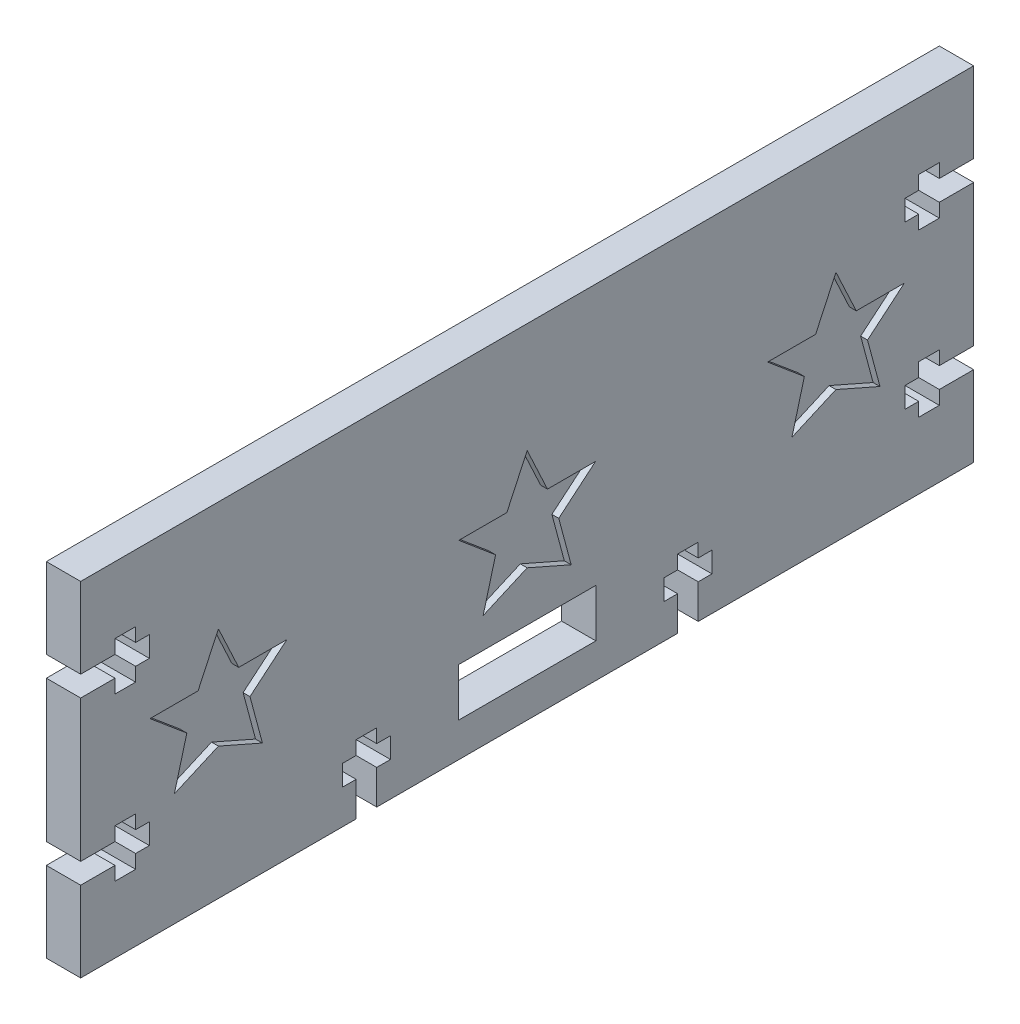
SolidWorks part; units mm, degrees
ref_plane "Front Plane" through (0, 0, 0) normal (0, 0, 1) x (1, 0, 0)
ref_plane "Top Plane" through (0, 0, 0) normal (0, 1, 0) x (1, 0, 0)
ref_plane "Right Plane" through (0, 0, 0) normal (1, 0, 0) x (0, 0, -1)
sketch "Sketch1" plane through (0, 0, 0) normal (1, 0, 0) x (0, 0, -1)
  line L0 (0, -14.859) -> (0, -18.669) construction
  line L1 (0, 0) -> (165.1, 0)
  line L2 (0, 0) -> (0, -14.859)
  line L3 (0, -63.5) -> (165.1, -63.5)
  line L4 (165.1, 0) -> (165.1, -14.859)
  line L5 (0, -18.669) -> (6.35, -18.669)
  line L6 (0, -18.669) -> (0, -14.859) construction
  line L7 (0, -14.859) -> (6.35, -14.859)
  line L8 (12.7, -18.669) -> (12.7, -14.859)
  line L9 (0, -48.641) -> (6.35, -48.641)
  line L10 (0, -48.641) -> (0, -44.831) construction
  line L11 (0, -44.831) -> (6.35, -44.831)
  line L12 (12.7, -48.641) -> (12.7, -44.831)
  line L13 (6.35, -12.319) -> (10.16, -12.319)
  line L14 (6.35, -12.319) -> (6.35, -14.859)
  line L15 (6.35, -21.209) -> (10.16, -21.209)
  line L16 (10.16, -12.319) -> (10.16, -14.859)
  line L17 (6.35, -42.291) -> (10.16, -42.291)
  line L18 (6.35, -42.291) -> (6.35, -44.831)
  line L19 (6.35, -51.181) -> (10.16, -51.181)
  line L20 (10.16, -42.291) -> (10.16, -44.831)
  line L21 (165.1, -14.859) -> (158.75, -14.859)
  line L22 (165.1, -14.859) -> (165.1, -18.669) construction
  line L23 (165.1, -18.669) -> (158.75, -18.669)
  line L24 (152.4, -14.859) -> (152.4, -18.669)
  line L25 (154.94, -12.319) -> (158.75, -12.319)
  line L26 (154.94, -12.319) -> (154.94, -14.859)
  line L27 (154.94, -21.209) -> (158.75, -21.209)
  line L28 (158.75, -12.319) -> (158.75, -14.859)
  line L29 (165.1, -44.831) -> (158.75, -44.831)
  line L30 (165.1, -44.831) -> (165.1, -48.641) construction
  line L31 (165.1, -48.641) -> (158.75, -48.641)
  line L32 (152.4, -44.831) -> (152.4, -48.641)
  line L33 (154.94, -42.291) -> (158.75, -42.291)
  line L34 (154.94, -42.291) -> (154.94, -44.831)
  line L35 (154.94, -51.181) -> (158.75, -51.181)
  line L36 (158.75, -42.291) -> (158.75, -44.831)
  line L37 (0, -18.669) -> (0, -44.831)
  line L38 (6.35, -14.859) -> (6.35, -18.669) construction
  line L39 (6.35, -18.669) -> (6.35, -21.209)
  line L40 (10.16, -14.859) -> (10.16, -18.669) construction
  line L41 (10.16, -18.669) -> (10.16, -21.209)
  line L42 (6.35, -14.859) -> (10.16, -14.859) construction
  line L43 (10.16, -14.859) -> (12.7, -14.859)
  line L44 (6.35, -18.669) -> (10.16, -18.669) construction
  line L45 (10.16, -18.669) -> (12.7, -18.669)
  line L46 (0, -44.831) -> (0, -48.641) construction
  line L47 (0, -48.641) -> (0, -63.5)
  line L48 (6.35, -44.831) -> (6.35, -48.641) construction
  line L49 (6.35, -48.641) -> (6.35, -51.181)
  line L50 (10.16, -44.831) -> (10.16, -48.641) construction
  line L51 (10.16, -48.641) -> (10.16, -51.181)
  line L52 (6.35, -44.831) -> (10.16, -44.831) construction
  line L53 (10.16, -44.831) -> (12.7, -44.831)
  line L54 (6.35, -48.641) -> (10.16, -48.641) construction
  line L55 (10.16, -48.641) -> (12.7, -48.641)
  line L56 (165.1, -44.831) -> (165.1, -48.641) construction
  line L57 (165.1, -48.641) -> (165.1, -63.5)
  line L58 (158.75, -44.831) -> (158.75, -48.641) construction
  line L59 (158.75, -48.641) -> (158.75, -51.181)
  line L60 (154.94, -44.831) -> (154.94, -48.641) construction
  line L61 (154.94, -48.641) -> (154.94, -51.181)
  line L62 (158.75, -44.831) -> (154.94, -44.831) construction
  line L63 (154.94, -44.831) -> (152.4, -44.831)
  line L64 (158.75, -48.641) -> (154.94, -48.641) construction
  line L65 (154.94, -48.641) -> (152.4, -48.641)
  line L66 (165.1, -14.859) -> (165.1, -18.669) construction
  line L67 (165.1, -18.669) -> (165.1, -44.831)
  line L68 (158.75, -14.859) -> (158.75, -18.669) construction
  line L69 (158.75, -18.669) -> (158.75, -21.209)
  line L70 (154.94, -14.859) -> (154.94, -18.669) construction
  line L71 (154.94, -18.669) -> (154.94, -21.209)
  line L72 (158.75, -14.859) -> (154.94, -14.859) construction
  line L73 (154.94, -14.859) -> (152.4, -14.859)
  line L74 (158.75, -18.669) -> (154.94, -18.669) construction
  line L75 (154.94, -18.669) -> (152.4, -18.669)
  point P21 (12.7, -16.764)
  point P22 (12.7, -46.736)
  point P47 (152.4, -46.736)
  point P52 (152.4, -16.764)
  dimension "D1" = 165.1
  dimension "D2" = 63.5
  dimension "D3" = 16.764
  dimension "D4" = 16.764
  dimension "D5" = 12.7
  dimension "D6" = 3.81
  dimension "D7" = 12.7
  dimension "D8" = 3.81
  dimension "D9" = 8.89
  dimension "D10" = 3.81
  dimension "D11" = 2.54
  dimension "D12" = 6.35
  dimension "D13" = 2.54
  dimension "D14" = 6.35
  dimension "D15" = 3.81
  dimension "D16" = 12.7
  dimension "D17" = 3.81
  dimension "D18" = 8.89
  dimension "D19" = 3.81
  dimension "D20" = 2.54
  dimension "D21" = 6.35
  dimension "D22" = 8.89
  dimension "D23" = 16.764
  dimension "D24" = 8.89
  dimension "D25" = 3.81
  dimension "D26" = 3.81
  dimension "D27" = 12.7
  dimension "D28" = 2.54
  dimension "D29" = 6.35
  dimension "D30" = 16.764
extrude "Boss-Extrude1" add sketch "Sketch1" along normal blind 6.35
sketch "Sketch2" plane through (6.35, 0, 0) normal (1, 0, 0) x (0, 0, -1)
  line L0 (0, -63.5) -> (165.1, -63.5) construction
  line L1 (50.927, -63.5) -> (54.737, -63.5)
  line L2 (50.927, -63.5) -> (50.927, -57.15)
  line L3 (50.927, -50.8) -> (54.737, -50.8)
  line L4 (54.737, -63.5) -> (54.737, -57.15)
  line L5 (50.927, -53.34) -> (54.737, -53.34) construction
  line L6 (48.387, -53.34) -> (50.927, -53.34)
  line L7 (48.387, -53.34) -> (48.387, -57.15)
  line L8 (48.387, -57.15) -> (50.927, -57.15)
  line L9 (57.277, -53.34) -> (57.277, -57.15)
  line L10 (110.363, -63.5) -> (114.173, -63.5)
  line L11 (110.363, -63.5) -> (110.363, -57.15)
  line L12 (110.363, -50.8) -> (114.173, -50.8)
  line L13 (114.173, -63.5) -> (114.173, -57.15)
  line L14 (107.823, -53.34) -> (110.363, -53.34)
  line L15 (107.823, -53.34) -> (107.823, -57.15)
  line L16 (107.823, -57.15) -> (110.363, -57.15)
  line L17 (116.713, -53.34) -> (116.713, -57.15)
  line L18 (54.737, -53.34) -> (57.277, -53.34)
  line L19 (50.927, -57.15) -> (54.737, -57.15) construction
  line L20 (54.737, -57.15) -> (57.277, -57.15)
  line L21 (50.927, -57.15) -> (50.927, -53.34) construction
  line L22 (50.927, -53.34) -> (50.927, -50.8)
  line L23 (54.737, -57.15) -> (54.737, -53.34) construction
  line L24 (54.737, -53.34) -> (54.737, -50.8)
  line L25 (110.363, -53.34) -> (114.173, -53.34) construction
  line L26 (114.173, -53.34) -> (116.713, -53.34)
  line L27 (110.363, -57.15) -> (114.173, -57.15) construction
  line L28 (114.173, -57.15) -> (116.713, -57.15)
  line L29 (110.363, -57.15) -> (110.363, -53.34) construction
  line L30 (110.363, -53.34) -> (110.363, -50.8)
  line L31 (114.173, -57.15) -> (114.173, -53.34) construction
  line L32 (114.173, -53.34) -> (114.173, -50.8)
  point P18 (52.832, -50.8)
  point P19 (112.268, -50.8)
  point P20 (82.55, -63.5)
  dimension "D1" = 12.7
  dimension "D2" = 3.81
  dimension "D3" = 3.81
  dimension "D4" = 8.89
  dimension "D5" = 2.54
  dimension "D6" = 6.35
  dimension "D7" = 3.81
  dimension "D8" = 8.89
  dimension "D9" = 3.81
  dimension "D10" = 12.7
  dimension "D11" = 2.54
  dimension "D12" = 6.35
  dimension "D13" = 59.436
  dimension "D14" = 29.718
extrude "Cut-Extrude1" cut sketch "Sketch2" against normal through all
sketch "Sketch3" plane through (6.35, 0, 0) normal (1, 0, 0) x (0, 0, -1)
  line L0 (25.4635, -63.5) -> (25.4635, 0) construction
  line L1 (165.1, 0) -> (0, 0) construction
  line L2 (0, -63.5) -> (50.927, -63.5) construction
  line L3 (82.55, -20.32) -> (78.7929, -28.3771)
  line L4 (139.6365, 0) -> (139.6365, -63.5) construction
  line L5 (114.173, -63.5) -> (165.1, -63.5) construction
  line L6 (78.7929, -28.3771) -> (69.9029, -28.3771)
  line L7 (82.55, -63.5) -> (82.55, 0) construction
  line L8 (54.737, -63.5) -> (110.363, -63.5) construction
  line L9 (25.4635, -20.32) -> (21.7064, -28.3771)
  line L10 (21.7064, -28.3771) -> (12.8164, -28.3771)
  line L11 (12.8164, -28.3771) -> (19.6266, -34.0915)
  line L12 (19.6266, -34.0915) -> (17.3257, -42.6785)
  line L13 (17.3257, -42.6785) -> (25.4635, -39.0998)
  line L14 (25.4635, -39.0998) -> (33.6013, -42.6785)
  line L15 (33.6013, -42.6785) -> (31.3004, -34.0915)
  line L16 (31.3004, -34.0915) -> (38.1106, -28.3771)
  line L17 (38.1106, -28.3771) -> (29.2206, -28.3771)
  line L18 (29.2206, -28.3771) -> (25.4635, -20.32)
  line L19 (69.9029, -28.3771) -> (76.7131, -34.0915)
  line L20 (76.7131, -34.0915) -> (74.4122, -42.6785)
  line L21 (74.4122, -42.6785) -> (82.55, -39.0998)
  line L22 (82.55, -39.0998) -> (90.6878, -42.6785)
  line L23 (90.6878, -42.6785) -> (88.3869, -34.0915)
  line L24 (88.3869, -34.0915) -> (95.1971, -28.3771)
  line L25 (95.1971, -28.3771) -> (86.3071, -28.3771)
  line L26 (86.3071, -28.3771) -> (82.55, -20.32)
  line L27 (139.6365, -20.32) -> (135.8794, -28.3771)
  line L28 (135.8794, -28.3771) -> (126.9894, -28.3771)
  line L29 (126.9894, -28.3771) -> (133.7996, -34.0915)
  line L30 (133.7996, -34.0915) -> (131.4987, -42.6785)
  line L31 (131.4987, -42.6785) -> (139.6365, -39.0998)
  line L32 (139.6365, -39.0998) -> (147.7743, -42.6785)
  line L33 (147.7743, -42.6785) -> (145.4734, -34.0915)
  line L34 (145.4734, -34.0915) -> (152.2836, -28.3771)
  line L35 (152.2836, -28.3771) -> (143.3936, -28.3771)
  line L36 (143.3936, -28.3771) -> (139.6365, -20.32)
  dimension "D1" = 8.89
  dimension "D2" = 8.89
  dimension "D3" = 8.89
  dimension "D4" = 8.89
  dimension "D5" = 8.89
  dimension "D6" = 8.89
  dimension "D7" = 8.89
  dimension "D8" = 40
  dimension "D9" = 115
  dimension "D10" = 8.89
  dimension "D11" = 20.32
  dimension "D12" = 25
  dimension "D13" = 25
  dimension "D14" = 66.262
  dimension "D15" = 66.262
  dimension "D16" = 8.89
  dimension "D17" = 8.89
  dimension "D18" = 8.89
  dimension "D19" = 8.89
  dimension "D20" = 8.89
  dimension "D21" = 8.89
  dimension "D22" = 8.89
  dimension "D23" = 8.89
  dimension "D24" = 8.89
  dimension "D25" = 40
  dimension "D26" = 115
  dimension "D27" = 8.89
  dimension "D28" = 8.89
  dimension "D29" = 8.89
  dimension "D30" = 20.32
  dimension "D31" = 25
  dimension "D32" = 25
  dimension "D33" = 66.262
  dimension "D34" = 66.262
  dimension "D35" = 8.89
  dimension "D36" = 8.89
  dimension "D37" = 8.89
  dimension "D38" = 8.89
  dimension "D39" = 8.89
  dimension "D40" = 8.89
  dimension "D41" = 8.89
  dimension "D42" = 40
  dimension "D43" = 115
  dimension "D44" = 8.89
  dimension "D45" = 20.32
  dimension "D46" = 8.89
  dimension "D47" = 8.89
  dimension "D48" = 25
  dimension "D49" = 25
  dimension "D50" = 66.262
  dimension "D51" = 66.262
extrude "Cut-Extrude2" cut sketch "Sketch3" against normal blind 1.27
sketch "Sketch4" plane through (6.35, 0, 0) normal (1, 0, 0) x (0, 0, -1)
  line L0 (54.737, -63.5) -> (110.363, -63.5) construction
  line L1 (69.85, -48.26) -> (95.25, -48.26)
  line L2 (69.85, -48.26) -> (69.85, -57.15)
  line L3 (69.85, -57.15) -> (95.25, -57.15)
  line L4 (95.25, -48.26) -> (95.25, -57.15)
  line L6 (82.55, -48.26) -> (82.55, -63.5) construction
  dimension "D1" = 8.89
  dimension "D2" = 25.4
  dimension "D3" = 6.35
extrude "Cut-Extrude3" cut sketch "Sketch4" against normal through all
